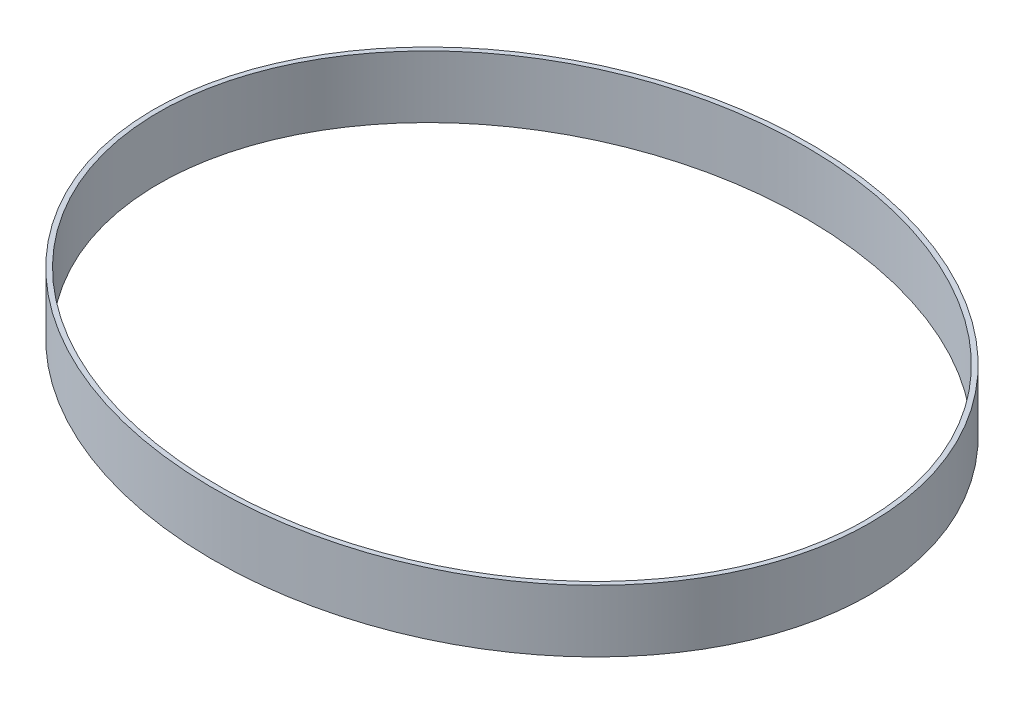
SolidWorks part; units mm, degrees
ref_plane "Front Plane" through (0, 0, 0) normal (0, 0, 1) x (1, 0, 0)
ref_plane "Top Plane" through (0, 0, 0) normal (0, 1, 0) x (1, 0, 0)
ref_plane "Right Plane" through (0, 0, 0) normal (1, 0, 0) x (0, 0, -1)
sketch "Sketch1" plane through (0, 0, 0) normal (0, 1, 0) x (1, 0, 0)
  ellipse E0 centre (0, 0) end of major axis (75, 0) minor radius 62.5
  ellipse E1 centre (0, 0) end of major axis (74, 0) minor radius 61.5
  dimension "D1" = 150
  dimension "D2" = 125
  dimension "D3" = 123
  dimension "D4" = 148
extrude "Boss-Extrude1" add sketch "Sketch1" along normal blind 13
